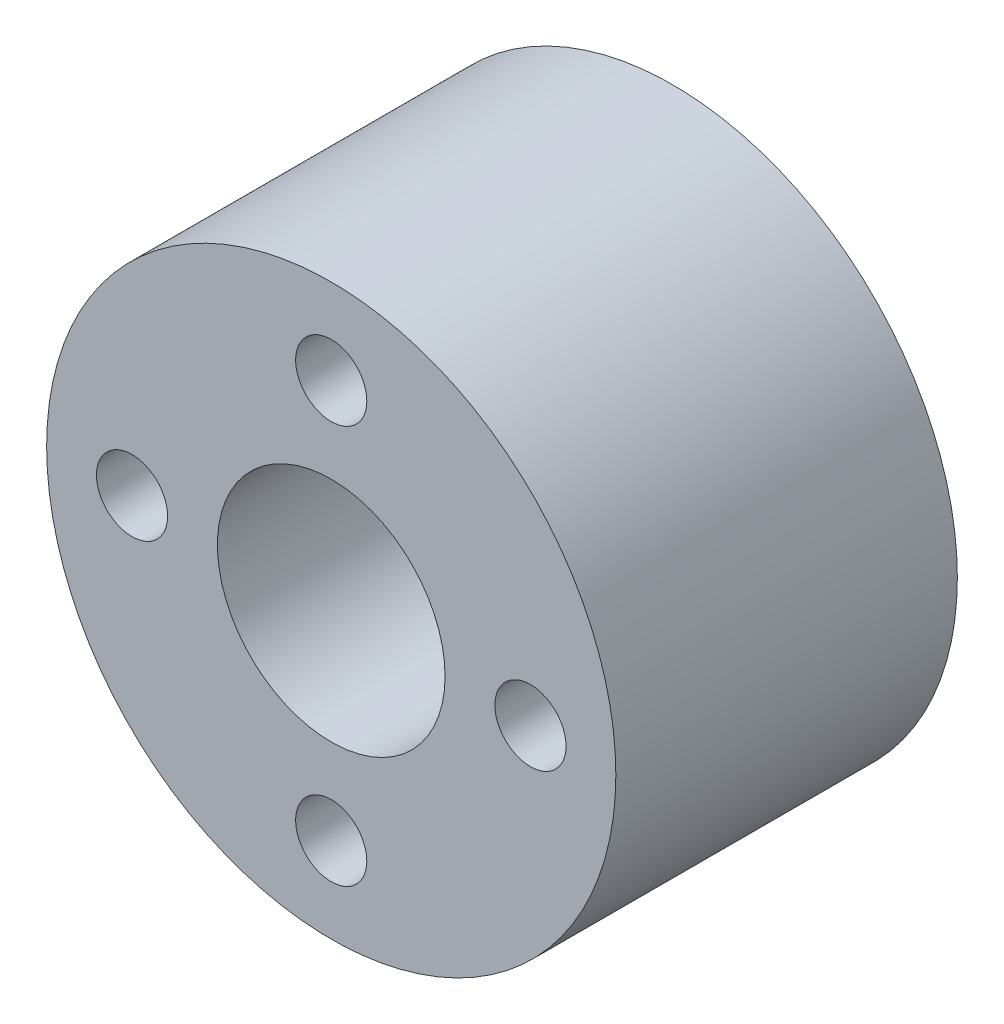
SolidWorks part; units mm, degrees
ref_plane "前视基准面" through (0, 0, 0) normal (0, 0, 1) x (1, 0, 0)
ref_plane "上视基准面" through (0, 0, 0) normal (0, 1, 0) x (1, 0, 0)
ref_plane "右视基准面" through (0, 0, 0) normal (1, 0, 0) x (0, 0, -1)
sketch "草图1" plane through (0, 0, 0) normal (0, 0, 1) x (1, 0, 0)
  circle A0 centre (0, 0) radius 10
  circle A1 centre (0, 0) radius 4
  circle A2 centre (7, 0) radius 1.25
  circle A3 centre (0, -7) radius 1.25
  circle A4 centre (-7, 0) radius 1.25
  circle A5 centre (0, 7) radius 1.25
  dimension "D1" = 20
  dimension "D2" = 8
  dimension "D3" = 7
  dimension "D4" = 2.5
  dimension "D5" = 4
extrude "凸台-拉伸1" add sketch "草图1" along normal blind 12
